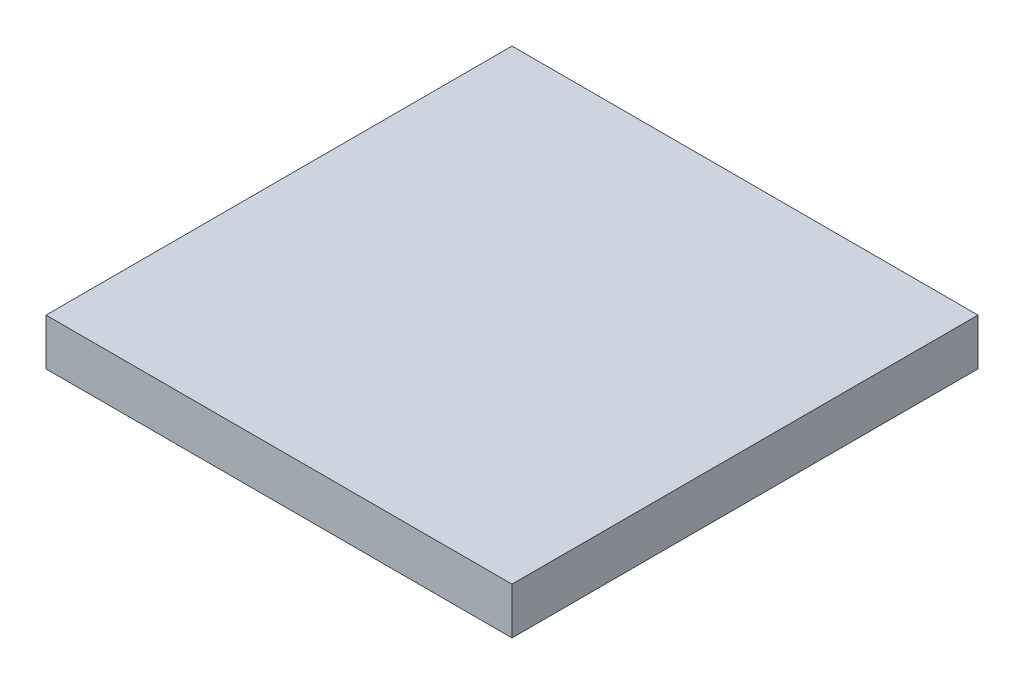
SolidWorks part; units mm, degrees
ref_plane "Alzado" through (0, 0, 0) normal (0, 0, 1) x (1, 0, 0)
ref_plane "Planta" through (0, 0, 0) normal (0, 1, 0) x (1, 0, 0)
ref_plane "Vista lateral" through (0, 0, 0) normal (1, 0, 0) x (0, 0, -1)
sketch "Croquis1" plane through (0, 0, 0) normal (0, 1, 0) x (1, 0, 0)
  line L1 (0, 0) -> (100, 0)
  line L2 (0, 0) -> (0, 100)
  line L3 (0, 100) -> (100, 100)
  line L4 (100, 0) -> (100, 100)
  dimension "D1" = 100
  dimension "D2" = 100
extrude "Saliente-Extruir1" add sketch "Croquis1" along normal blind 10
